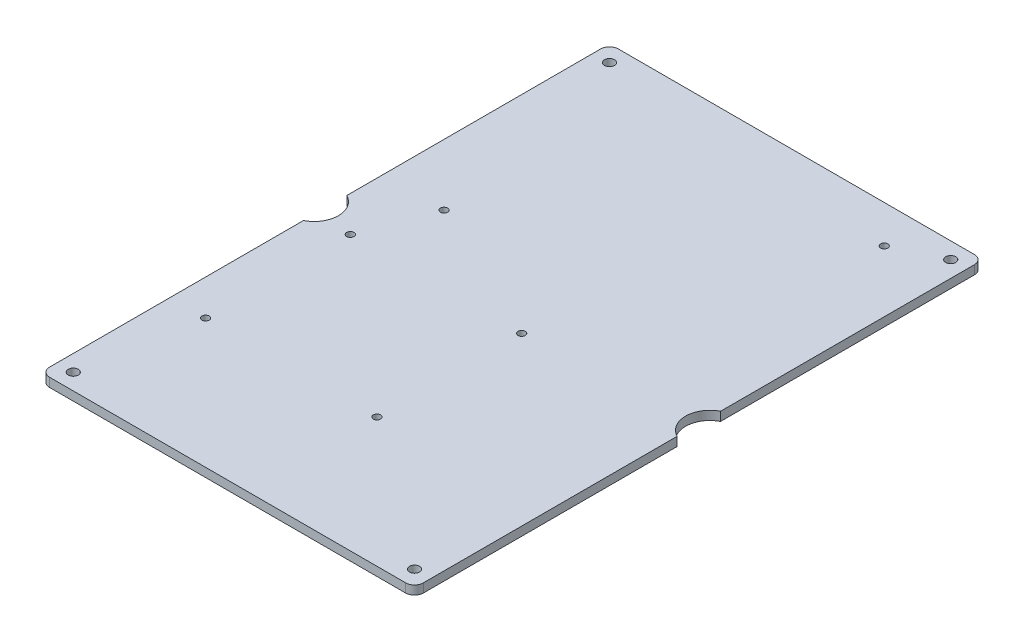
SolidWorks part; units mm, degrees
material "Acrylic (Medium-high impact)"
ref_plane "Front Plane" through (0, 0, 0) normal (0, 0, 1) x (1, 0, 0)
ref_plane "Top Plane" through (0, 0, 0) normal (0, 1, 0) x (1, 0, 0)
ref_plane "Right Plane" through (0, 0, 0) normal (1, 0, 0) x (0, 0, -1)
sketch "Sketch1" plane through (0, 0, 0) normal (0, 1, 0) x (1, 0, 0)
  line L0 (63.25, 96.25) -> (-63.25, 96.25)
  line L1 (57.75, -90.75) -> (-57.75, -90.75) construction
  line L2 (57.75, -90.75) -> (57.75, 90.75) construction
  line L3 (57.75, 90.75) -> (-57.75, 90.75) construction
  line L4 (-57.75, -90.75) -> (-57.75, 90.75) construction
  line L5 (57.75, -90.75) -> (-57.75, 90.75) construction
  line L6 (57.75, 90.75) -> (-57.75, -90.75) construction
  line L7 (-63.25, -96.25) -> (-63.25, 96.25)
  line L8 (63.25, -96.25) -> (-63.25, -96.25)
  line L9 (63.25, -96.25) -> (63.25, 96.25)
  point P0 (0, 0)
  dimension "D1" = 115.5
  dimension "D2" = 181.5
  dimension "D3" = 5.5
extrude "Boss-Extrude1" add sketch "Sketch1" along normal blind 3
sketch "Sketch2" plane through (0, 3, 0) normal (0, 1, 0) x (1, 0, 0)
  line L0 (0, 0) -> (50000, 0) construction
  line L1 (0, 0) -> (0, 25.5173) construction
  circle A0 centre (67, 0) radius 8.25
  dimension "D1" = 16.5
  dimension "D2" = 67
extrude "Cut-Extrude1" cut sketch "Sketch2" against normal up to next
mirror "Mirror1" about plane through (0, 0, 0) normal (1, 0, 0) of "Cut-Extrude1"
hole_wizard "M3 Clearance Hole1" positions "Sketch3" profile "Sketch4" hole size "M3" standard "ISO" end condition through all
sketch "Sketch3" plane through (0, 3, 0) normal (0, 1, 0) x (1, 0, 0)
  line L1 (57.75, -90.75) -> (-57.75, -90.75)
  line L2 (57.75, -90.75) -> (57.75, 90.75)
  line L3 (57.75, 90.75) -> (-57.75, 90.75)
  line L4 (-57.75, -90.75) -> (-57.75, 90.75)
  line L5 (57.75, -90.75) -> (-57.75, 90.75) construction
  line L6 (57.75, 90.75) -> (-57.75, -90.75) construction
  point P2 (-57.75, 90.75)
  point P51 (57.75, -90.75)
  point P52 (57.75, 90.75)
  point P53 (-57.75, -90.75)
  dimension "D1" = 115.5
  dimension "D2" = 181.5
sketch "Sketch4" plane through (-57.75, 3, -90.75) normal (1, 0, 0) x (0, 0, 1)
  line L0 (0, 0) -> (0, 3)
  line L1 (0, 3) -> (1.7, 3)
  line L2 (1.7, 3) -> (1.7, 0)
  line L5 (1.7, 0) -> (0, 0)
  line L11 (0, -6.35) -> (0, 107.95) construction
  dimension "Thru Hole Dia." = 3.4
  dimension "Thru Hole Depth" = 3
fillet "Fillet1" radius 3 4 edges at (-63.25, 1.5, 96.25) (63.25, 1.5, 96.25) (63.25, 1.5, -96.25) (-63.25, 1.5, -96.25)
hole_wizard "M3 Tapped Hole1" positions "Sketch6" profile "Sketch5" tap size "M3" standard "ISO" end condition through all
sketch "Sketch6" plane through (0, 0, 0) normal (0, -1, 0) x (-1, 0, 0)
  circle A0 centre (-6.773, -52.5) radius 1.1727 construction
  circle A1 centre (-6.773, -52.5) radius 1.1727
  circle A2 centre (-42.5, 83.5) radius 1.1727 construction
  circle A3 centre (42.5, 19.5) radius 1.1727 construction
  circle A4 centre (-6.773, -3.5) radius 1.1727 construction
  circle A5 centre (51.227, -3.5) radius 1.1727 construction
  circle A6 centre (51.227, -52.5) radius 1.1727 construction
  circle A7 centre (-42.5, 83.5) radius 1.1727
  circle A8 centre (42.5, 19.5) radius 1.1727
  circle A9 centre (-6.773, -3.5) radius 1.1727
  circle A10 centre (51.227, -3.5) radius 1.1727
  circle A11 centre (51.227, -52.5) radius 1.1727
  point P1 (-6.773, -52.5)
  point P4 (-42.5, 83.5)
  point P6 (42.5, 19.5)
  point P8 (-6.773, -3.5)
  point P10 (51.227, -3.5)
  point P12 (51.227, -52.5)
sketch "Sketch5" plane through (6.773, 0, 52.5) normal (1, 0, 0) x (0, 0, -1)
  line L0 (0, 0) -> (0, 3)
  line L1 (0, 3) -> (1.23, 3)
  line L2 (1.23, 3) -> (1.23, 0)
  line L5 (1.23, 0) -> (0, 0)
  line L11 (0, -6.35) -> (0, 107.95) construction
  dimension "Thru Tap Drill Dia." = 2.46
  dimension "Thru Tap Drill Depth" = 3
cosmetic thread "Hole Thread1" parameters "D2"=3
cosmetic thread "Hole Thread2" parameters "D2"=3
cosmetic thread "Hole Thread3" parameters "D2"=3
cosmetic thread "Hole Thread4" parameters "D2"=3
cosmetic thread "Hole Thread5" parameters "D2"=3
cosmetic thread "Hole Thread6" parameters "D2"=3
